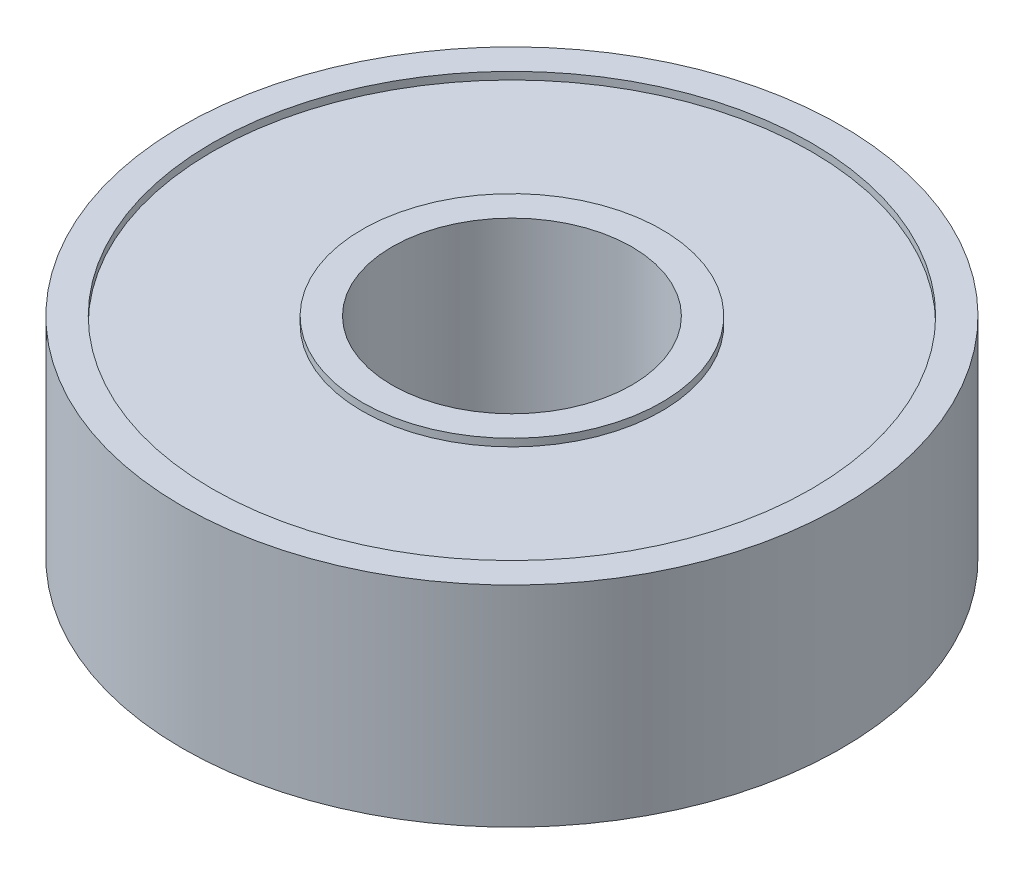
SolidWorks part; units mm, degrees
ref_plane "Front Plane" through (0, 0, 0) normal (0, 0, 1) x (1, 0, 0)
ref_plane "Top Plane" through (0, 0, 0) normal (0, 1, 0) x (1, 0, 0)
ref_plane "Right Plane" through (0, 0, 0) normal (1, 0, 0) x (0, 0, -1)
sketch "Sketch1" plane through (0, 0, 0) normal (0, 1, 0) x (1, 0, 0)
  circle A0 centre (0, 0) radius 4
  circle A1 centre (0, 0) radius 11
  dimension "D1" = 8
  dimension "D2" = 22
extrude "Boss-Extrude1" add sketch "Sketch1" along normal blind 7
ref_axis "Axis1" through (0, 7, 0) along (0, -1, 0)
sketch "Sketch2" plane through (0, 0, 0) normal (0, 0, 1) x (1, 0, 0)
  line L0 (11, 7) -> (-11, 7) construction
  line L1 (-10, 7) -> (-5, 7)
  line L2 (-10, 7) -> (-10, 6.75)
  line L3 (-10, 6.75) -> (-5, 6.75)
  line L4 (-5, 7) -> (-5, 6.75)
  line L5 (-11, 0) -> (11, 0) construction
  line L6 (-10, 0) -> (-5, 0)
  line L7 (-10, 0) -> (-10, 0.25)
  line L8 (-10, 0.25) -> (-5, 0.25)
  line L9 (-5, 0) -> (-5, 0.25)
  line L10 (-11, 7) -> (-11, 0) construction
  line L12 (-4, 7) -> (-4, 0) construction
  dimension "D1" = 0.25
  dimension "D2" = 1
  dimension "D3" = 1
revolve "Cut-Revolve1" cut sketch "Sketch2" angle 360 about axis through (0, 7, 0) along (0, -1, 0)
